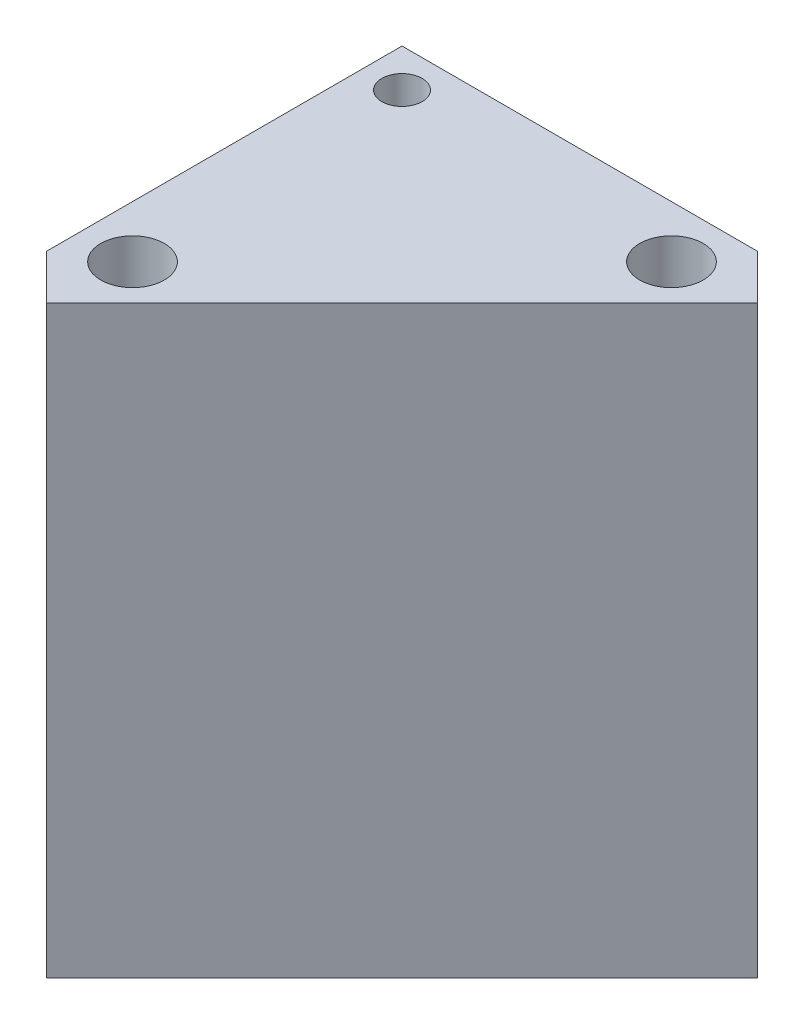
SolidWorks part; units mm, degrees
ref_plane "Front Plane" through (0, 0, 0) normal (0, 0, 1) x (1, 0, 0)
ref_plane "Top Plane" through (0, 0, 0) normal (0, 1, 0) x (1, 0, 0)
ref_plane "Right Plane" through (0, 0, 0) normal (1, 0, 0) x (0, 0, -1)
sketch "Sketch1" plane through (0, 0, 0) normal (0, 1, 0) x (1, 0, 0)
  line L0 (0, 0) -> (0, -28)
  line L1 (0, 0) -> (28, 0)
  line L2 (28, 0) -> (31.5355, -3.5355)
  line L3 (31.5355, -3.5355) -> (3.5355, -31.5355)
  line L4 (3.5355, -31.5355) -> (0, -28)
  dimension "D1" = 28
  dimension "D2" = 28
  dimension "D3" = 135
  dimension "D4" = 135
  dimension "D5" = 5
extrude "Boss-Extrude1" add sketch "Sketch1" along normal blind 46
sketch "Sketch2" plane through (0, 0, 0) normal (0, -1, 0) x (1, 0, 0)
  line L0 (0, 0) -> (0, 28) construction
  line L1 (0, 20) -> (0, 0)
  line L2 (0, 0) -> (20, 0)
  arc A0 (0, 20) -> (20, 0) centre (0, 0) cw
  dimension "D1" = 20
extrude "Cut-Extrude3" cut sketch "Sketch2" against normal blind 25 from offset 16 offset against normal yes
sketch "Sketch3" plane through (0, 46, 0) normal (0, 1, 0) x (1, 0, 0)
  line L0 (0, 0) -> (0, -28) construction
  line L1 (28, 0) -> (0, 0) construction
  circle A0 centre (3, -3) radius 1.5875
  dimension "D1" = 3.175
  dimension "D2" = 3
  dimension "D3" = 3
extrude "Cut-Extrude4" cut sketch "Sketch3" against normal through all
sketch "Sketch5" plane through (0, 46, 0) normal (0, 1, 0) x (1, 0, 0)
  line L0 (28.7071, -0.7071) -> (0.7071, -28.7071) construction
  line L1 (31.5355, -3.5355) -> (28, 0) construction
  line L2 (0, -28) -> (3.5355, -31.5355) construction
  line L3 (0, 0) -> (17.5355, -17.5355) construction
  line L4 (3.5355, -31.5355) -> (31.5355, -3.5355) construction
  circle A0 centre (25.3137, -4.1005) radius 2.5
  circle A1 centre (4.1005, -25.3137) radius 2.5
  dimension "D1" = 5
  dimension "D2" = 4
  dimension "D3" = 30
extrude "Cut-Extrude5" cut sketch "Sketch5" against normal blind 10
